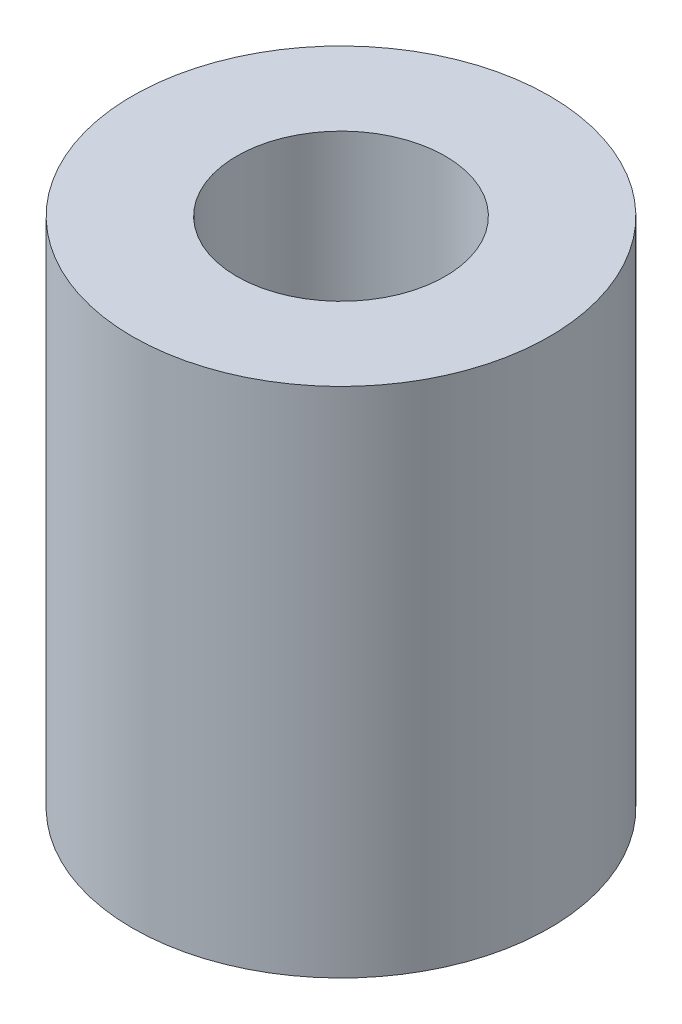
SolidWorks part; units mm, degrees
material "NEOPRENE"
ref_plane "Front Plane" through (0, 0, 0) normal (0, 0, 1) x (1, 0, 0)
ref_plane "Top Plane" through (0, 0, 0) normal (0, 1, 0) x (1, 0, 0)
ref_plane "Right Plane" through (0, 0, 0) normal (1, 0, 0) x (0, 0, -1)
sketch "Sketch1" plane through (0, 0, 0) normal (0, 1, 0) x (1, 0, 0)
  circle A0 centre (0, 0) radius 14
  circle A1 centre (0, 0) radius 7
  dimension "D1" = 14
  dimension "D2" = 28
extrude "Boss-Extrude1" add sketch "Sketch1" along normal blind 34.4
